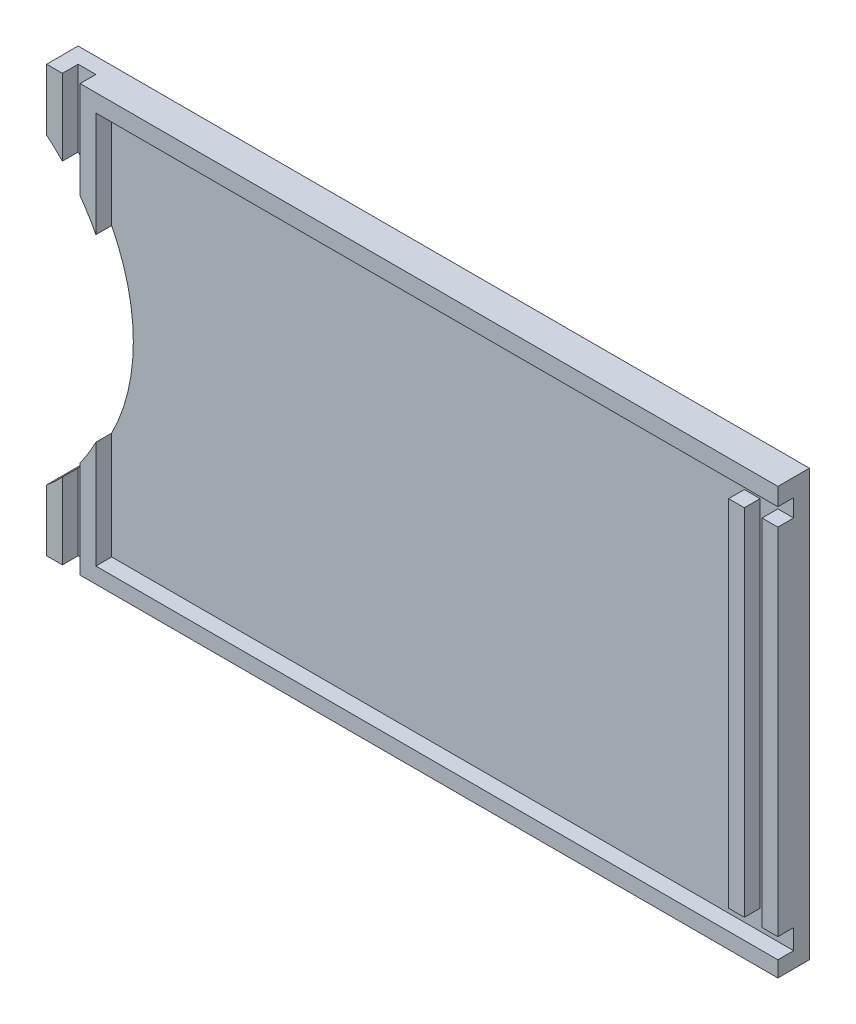
SolidWorks part; units mm, degrees
ref_plane "Front Plane" through (0, 0, 0) normal (0, 0, 1) x (1, 0, 0)
ref_plane "Top Plane" through (0, 0, 0) normal (0, 1, 0) x (1, 0, 0)
ref_plane "Right Plane" through (0, 0, 0) normal (1, 0, 0) x (0, 0, -1)
sketch "Sketch1" plane through (0, 0, 0) normal (0, 1, 0) x (1, 0, 0)
  line L0 (-63.4089, 20.488) -> (122.0911, 20.488)
  line L1 (122.0911, 20.488) -> (122.0911, 12.488)
  line L2 (122.0911, 12.488) -> (118.0911, 12.488)
  line L3 (118.0911, 12.488) -> (118.0911, 16.488)
  line L4 (118.0911, 16.488) -> (113.5911, 16.488)
  line L5 (113.5911, 16.488) -> (113.5911, 12.488)
  line L6 (113.5911, 12.488) -> (109.5911, 12.488)
  line L7 (109.5911, 12.488) -> (109.5911, 16.488)
  line L8 (-63.4089, 20.488) -> (-63.4089, 12.488)
  line L9 (-63.4089, 12.488) -> (-59.4089, 12.488)
  line L10 (-59.4089, 12.488) -> (-59.4089, 16.488)
  line L11 (-59.4089, 16.488) -> (-54.9089, 16.488)
  line L12 (-54.9089, 16.488) -> (-54.9089, 12.488)
  line L13 (-54.9089, 12.488) -> (-50.9089, 12.488)
  line L14 (-50.9089, 12.488) -> (-50.9089, 16.488)
  line L15 (-50.9089, 16.488) -> (109.5911, 16.488)
extrude "Boss-Extrude1" add sketch "Sketch1" along normal mid plane 108
sketch "Sketch7" plane through (0, 0, -12.488) normal (0, 0, 1) x (1, 0, 0)
  line L1 (122.0911, 54) -> (109.5486, 54)
  line L2 (122.0911, 54) -> (122.0911, 45.0585)
  line L3 (122.0911, 45.0585) -> (109.5486, 45.0585)
  line L4 (109.5486, 54) -> (109.5486, 45.0585)
extrude "Cut-Extrude4" cut sketch "Sketch7" against normal up to surface (4 mm away) up to face at (29.3411, 0, -16.488)
sketch "Sketch8" plane through (0, 0, -12.488) normal (0, 0, 1) x (1, 0, 0)
  line L1 (122.0911, -54) -> (109.5548, -54)
  line L2 (122.0911, -54) -> (122.0911, -44.9153)
  line L3 (122.0911, -44.9153) -> (109.5548, -44.9153)
  line L4 (109.5548, -54) -> (109.5548, -44.9153)
extrude "Cut-Extrude5" cut sketch "Sketch8" against normal up to surface (4 mm away) up to face at (-57.1589, 0, -16.488)
sketch "Sketch10" plane through (0, 0, -12.488) normal (0, 0, 1) x (1, 0, 0)
  line L0 (-63.4089, 54) -> (-63.4089, -54) construction
  line L1 (-63.4089, 0) -> (-95.4089, 0) construction
  circle A0 centre (-95.4089, 0) radius 50
  dimension "D1" = 32
  dimension "D2" = 100
extrude "Cut-Extrude6" cut sketch "Sketch10" against normal blind 10 contours A0
sketch "Sketch12" plane through (0, 0, -16.488) normal (0, 0, 1) x (1, 0, 0)
  line L0 (122.0911, -54) -> (122.0911, -44.9153) construction
  line L1 (-50.9089, -54) -> (122.0911, -54)
  line L2 (-50.9089, -54) -> (-50.9089, -50)
  line L3 (-50.9089, -50) -> (122.0911, -50)
  line L4 (122.0911, -54) -> (122.0911, -50)
  line L5 (122.0911, 45.0585) -> (122.0911, 54) construction
  line L6 (-50.9089, 54) -> (122.0911, 54)
  line L7 (-50.9089, 54) -> (-50.9089, 49.5293)
  line L8 (-50.9089, 49.5293) -> (122.0911, 49.5293)
  line L9 (122.0911, 54) -> (122.0911, 49.5293)
extrude "Boss-Extrude2" add sketch "Sketch12" along normal blind 4
